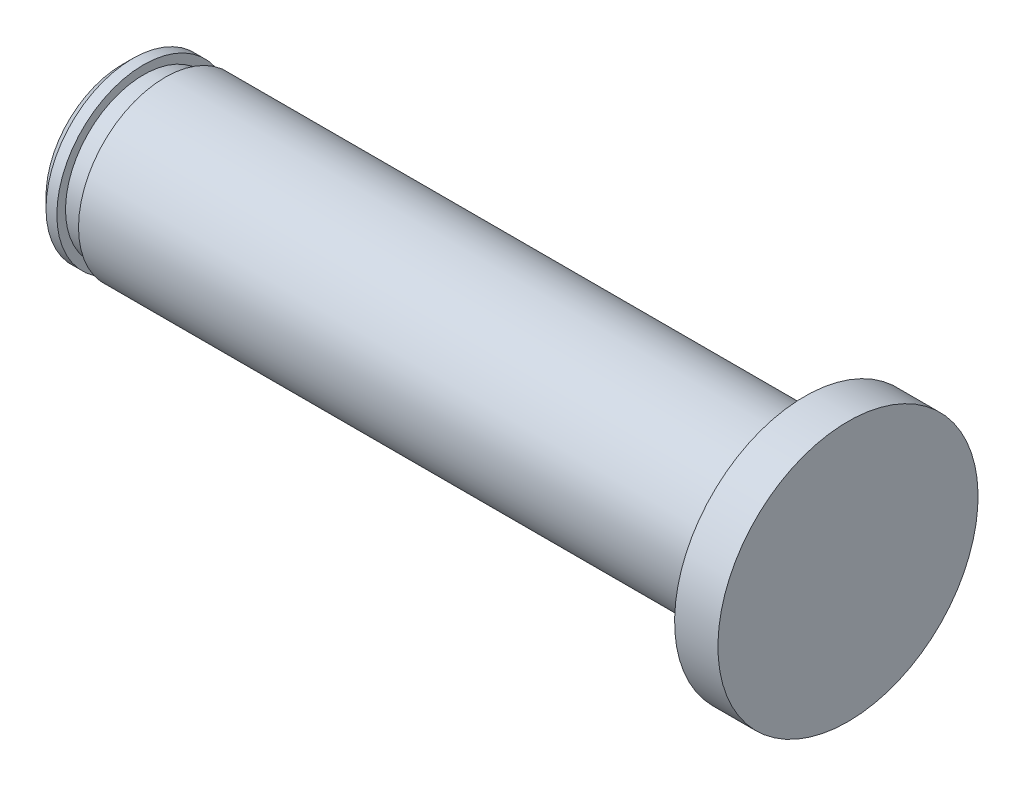
SolidWorks part; units mm, degrees
ref_plane "Спереди" through (0, 0, 0) normal (0, 0, 1) x (1, 0, 0)
ref_plane "Сверху" through (0, 0, 0) normal (0, 1, 0) x (1, 0, 0)
ref_plane "Справа" through (0, 0, 0) normal (1, 0, 0) x (0, 0, -1)
sketch "Эскиз1" plane through (0, 0, 0) normal (0, 0, 1) x (1, 0, 0)
  line L0 (0, 0) -> (-33.5, 0)
  line L1 (-33.5, 0) -> (-33.5, 4)
  line L2 (-33.5, 4) -> (-32.5, 4)
  line L3 (-32.5, 4) -> (-32.5, 3.6)
  line L4 (-32.5, 3.6) -> (-31.5, 3.6)
  line L5 (-31.5, 3.6) -> (-31.5, 4)
  line L6 (-31.5, 4) -> (-2, 4)
  line L7 (-2, 4) -> (-2, 6)
  line L8 (-2, 6) -> (0, 6)
  line L9 (0, 6) -> (0, 0)
  line L10 (-33.5, 0) -> (-24.8571, 0) construction
  line L11 (-32, 0) -> (-50032, 0) construction
  line L13 (-31.5, 4) -> (-31.5, -4) construction
  dimension "D1" = 8
  dimension "D3" = 2
  dimension "D4" = 2
  dimension "D5" = 1
  dimension "D6" = 1
  dimension "D7" = 7.2
revolve "Повернуть1" add sketch "Эскиз1" angle 360 about L10
chamfer "Фаска1" distance 0.5 angle 45 1 edges at (-33.5, -4, 0)
equation "\"Диаметр вала\" = 8  '!!!"
equation "\"Длина вала\" = 28"
equation "\"D1@Эскиз1\"=\"Диаметр вала\""
